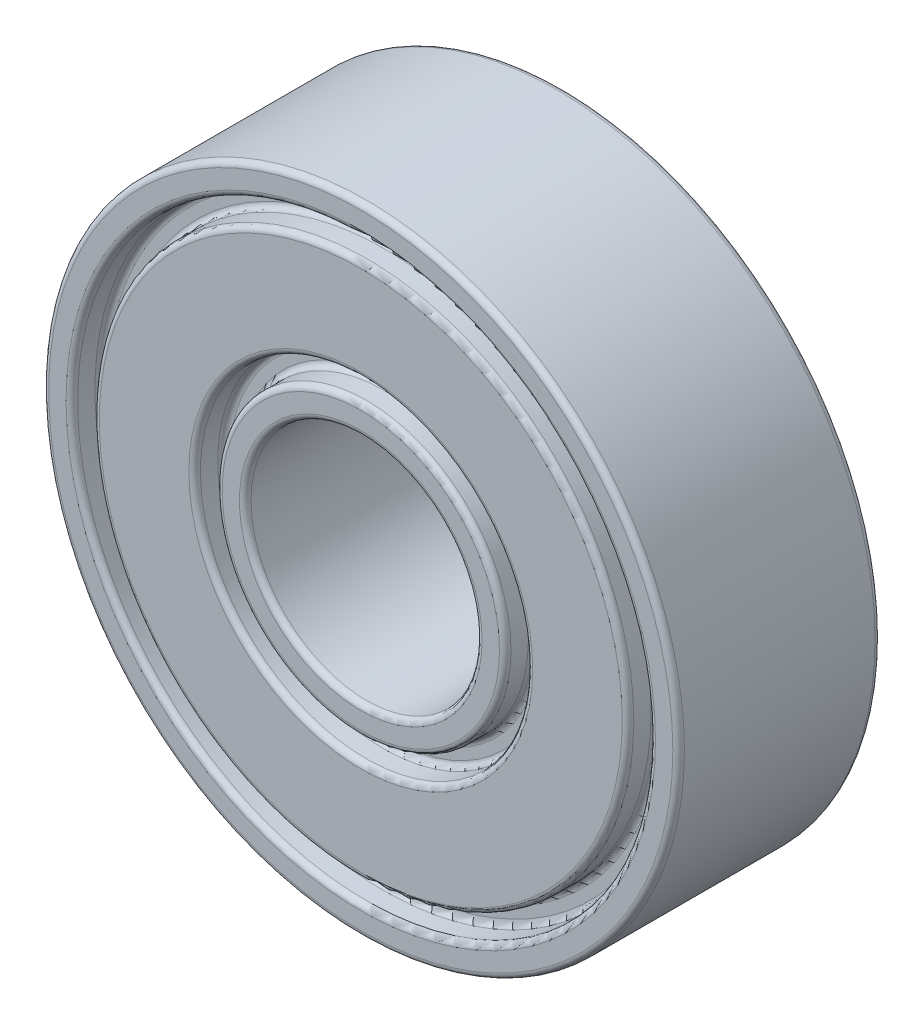
SolidWorks part; units mm, degrees
ref_plane "Front Plane" through (0, 0, 0) normal (0, 0, 1) x (1, 0, 0)
ref_plane "Top Plane" through (0, 0, 0) normal (0, 1, 0) x (1, 0, 0)
ref_plane "Right Plane" through (0, 0, 0) normal (1, 0, 0) x (0, 0, -1)
sketch "Sketch1" plane through (0, 0, 0) normal (0, 0, 1) x (1, 0, 0)
  circle A0 centre (0, 0) radius 11
  dimension "D1" = 22
extrude "Boss-Extrude1" add sketch "Sketch1" along normal blind 7
sketch "Sketch2" plane through (0, 0, 0) normal (0, 0, 1) x (1, 0, 0)
  circle A0 centre (0, 0) radius 4
  dimension "D1" = 8
extrude "Cut-Extrude1" cut sketch "Sketch2" along normal blind 7
sketch "Sketch3" plane through (0, 0, 0) normal (0, 0, 1) x (1, 0, 0)
  circle A0 centre (0, 0) radius 5
  circle A1 centre (0, 0) radius 5.75
  circle A2 centre (0, 0) radius 10
  circle A3 centre (0, 0) radius 9.25
  dimension "D1" = 20
  dimension "D2" = 18.5
  dimension "D3" = 10
  dimension "D4" = 11.5
extrude "Cut-Extrude2" cut sketch "Sketch3" along normal blind 1 contours A1 A0 | A2 A3
sketch "Sketch4" plane through (0, 0, 0) normal (0, 0, 1) x (1, 0, 0)
  circle A0 centre (0, 0) radius 5
  circle A1 centre (0, 0) radius 5.75
  circle A2 centre (0, 0) radius 9.25
  circle A3 centre (0, 0) radius 10
  dimension "D1" = 20
  dimension "D2" = 18.5
  dimension "D3" = 10
  dimension "D4" = 11.5
extrude "Cut-Extrude3" cut sketch "Sketch4" against normal blind 1 from surface at 7 contours A3 A2 | A1 A0 starting at face at (4, 0, 7)
fillet "Fillet1" radius 0.2 20 edges at (5.75, 0, 1) (5, 0, 1) (10, 0, 1) (9.25, 0, 1) (5.75, 0, 6) (5, 0, 6) (10, 0, 6) (9.25, 0, 6) (11, 0, 0) (10, 0, 0) (9.25, 0, 0) (5.75, 0, 0) (5, 0, 0) (4, 0, 0) (5, 0, 7) (4, 0, 7) (11, 0, 7) (10, 0, 7) (9.25, 0, 7) (5.75, 0, 7)
